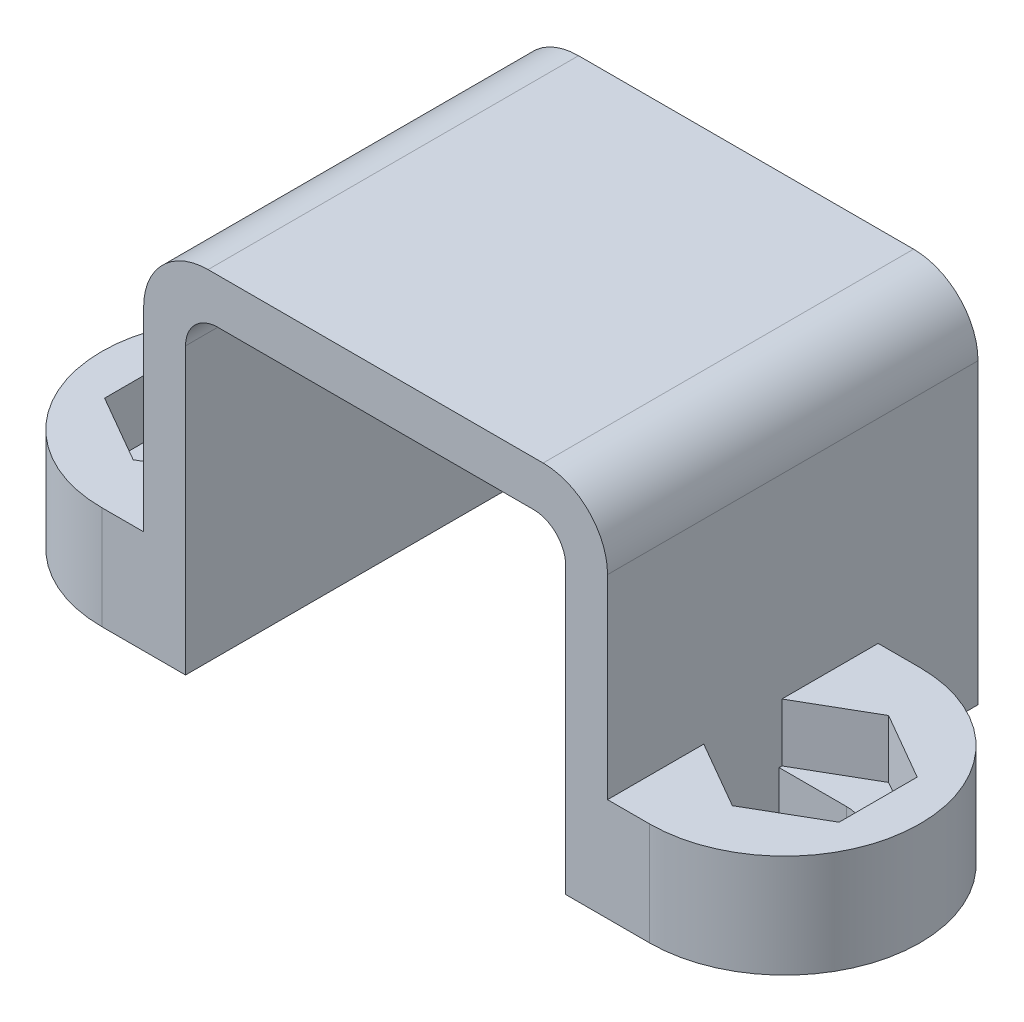
SolidWorks part; units mm, degrees
material "ABS PC"
ref_plane "前视基准面" through (0, 0, 0) normal (0, 0, 1) x (1, 0, 0)
ref_plane "上视基准面" through (0, 0, 0) normal (0, 1, 0) x (1, 0, 0)
ref_plane "右视基准面" through (0, 0, 0) normal (1, 0, 0) x (0, 0, -1)
sketch "草图1" plane through (0, 0, 0) normal (0, 0, 1) x (1, 0, 0)
  line L1 (14.4, 3.2) -> (14.4, 11.25)
  line L2 (14.4, 11.25) -> (0, 11.25)
  line L3 (0, 11.25) -> (0, 3.2)
  line L4 (1.3, 0) -> (1.3, 9.85)
  line L5 (1.3, 9.85) -> (13.1, 9.85)
  line L6 (13.1, 9.85) -> (13.1, 0)
  line L7 (0, 0) -> (1.3, 0)
  line L8 (19.9, 0) -> (19.9, 3.2)
  line L9 (19.9, 3.2) -> (14.4, 3.2)
  line L10 (0, 3.2) -> (-5.5, 3.2)
  line L11 (-5.5, 3.2) -> (-5.5, 0)
  line L12 (-5.5, 0) -> (0, 0)
  line L13 (14.4, 0) -> (19.9, 0)
  line L15 (13.1, 0) -> (14.4, 0)
  dimension "D1" = 14.4
  dimension "D2" = 9.85
  dimension "D3" = 11.25
  dimension "D4" = 11.8
  dimension "D5" = 11.25
  dimension "D6" = 3.2
  dimension "D7" = 3.2
  dimension "D8" = 5.5
  dimension "D9" = 5.5
extrude "凸台-拉伸1" add sketch "草图1" along normal blind 11.5
sketch "草图2" plane through (0, 3.2, 0) normal (0, 1, 0) x (1, 0, 0)
  line L3 (14.4, -11.5) -> (15.7, -11.5)
  line L5 (14.4, -11.5) -> (14.4, -3.1)
  line L6 (14.4, -11.5) -> (14.4, 0) construction
  line L7 (19.9, -11.5) -> (14.4, -11.5) construction
  line L9 (15.7, -3.1) -> (14.4, -3.1)
  arc A1 (15.7, -11.5) -> (15.7, -3.1) centre (15.7, -7.3) ccw
  line M8 (19.9, 0) -> (14.4, 0)
  line M9 (14.4, 0) -> (14.4, -11.5)
  line M10 (14.4, -11.5) -> (19.9, -11.5)
  line M11 (19.9, -11.5) -> (19.9, 0)
  dimension "D1" = 8.4
  dimension "D3" = 8.4
  dimension "D2" = 1.3
extrude "切除-拉伸1" cut sketch "草图2" against normal blind 11.5 contours A1 L9 M11 M8 M9 | A1 M10 M11
sketch "草图3" plane through (0, 3.2, 0) normal (0, 1, 0) x (1, 0, 0)
  line L0 (0, -11.5) -> (0, -3.1)
  line L1 (0, -11.5) -> (0, 0) construction
  line L2 (0, -11.5) -> (-5.5, -11.5) construction
  line L3 (0, -3.1) -> (-1.3, -3.1)
  line L5 (-1.3, -11.5) -> (0, -11.5)
  arc A0 (-1.3, -3.1) -> (-1.3, -11.5) centre (-1.3, -7.3) ccw
  line M5 (0, 0) -> (-5.5, 0)
  line M6 (-5.5, 0) -> (-5.5, -11.5)
  line M7 (-5.5, -11.5) -> (0, -11.5)
  line M8 (0, -11.5) -> (0, 0)
  dimension "D1" = 8.4
  dimension "D2" = 1.3
extrude "切除-拉伸2" cut sketch "草图3" against normal blind 11.5 contours A0 L3 M8 M5 M6 | A0 M6 M7
sketch "草图4" plane through (14.4, 0, 0) normal (1, 0, 0) x (0, 0, -1)
  line L1 (-3.1, 3.2) -> (-11.5, 3.2)
sketch "草图5" plane through (0, 3.2, 0) normal (0, 1, 0) x (1, 0, 0)
  line L1 (14.4, -3.1) -> (14.4, -11.5) construction
  line L2 (14.4, -3.1) -> (14.4, -7.3)
  line L4 (16.5, -6.175) -> (14.4, -6.175)
  line L5 (14.4, -6.175) -> (14.4, -8.425)
  line L6 (14.4, -8.425) -> (16.5, -8.425)
  line L7 (18.6, -6.0876) -> (16.5, -4.8751)
  line L8 (16.5, -4.8751) -> (14.4, -6.0876)
  line L9 (14.4, -6.0876) -> (14.4, -8.5124)
  line L10 (14.4, -8.5124) -> (16.5, -9.7249)
  line L11 (16.5, -9.7249) -> (18.6, -8.5124)
  line L12 (18.6, -8.5124) -> (18.6, -6.0876)
  arc A0 (16.5, -8.425) -> (16.5, -6.175) centre (16.5, -7.3) ccw
  circle A1 centre (16.5, -7.3) radius 2.1 construction
  dimension "D2" = 2.25
  dimension "D1" = 2.1
extrude "切除-拉伸3" cut sketch "草图5" against normal blind 1.8 contours L7 L8 L9 L10 L11 L12
sketch "草图7" plane through (0, 1.4, 0) normal (0, 1, 0) x (1, 0, 0)
  line L0 (14.4, -8.5124) -> (14.4, -6.0876)
  line L2 (16.5, -6.175) -> (14.4, -6.175)
  line L4 (14.4, -6.175) -> (14.4, -8.425)
  line L5 (16.5, -8.425) -> (14.4, -8.425)
  line L7 (16.5, -6.175) -> (14.4, -6.175)
  line L8 (16.5, -8.425) -> (14.4, -8.425)
  arc A0 (16.5, -8.425) -> (16.5, -6.175) centre (16.5, -7.3) ccw
  dimension "D2" = 2.25
sketch "草图8" plane through (0, 3.2, 0) normal (0, 1, 0) x (1, 0, 0)
  line L0 (0, -3.1) -> (0, -11.5)
  line L1 (0, -7.3) -> (-2.1, -7.3)
  line L2 (-4.2, -6.0876) -> (-4.2, -8.5124)
  line L4 (0, -6.0876) -> (-2.1, -4.8751)
  line L5 (-2.1, -4.8751) -> (-4.2, -6.0876)
  line L6 (-4.2, -6.0876) -> (-4.2, -8.5124)
  line L7 (-4.2, -8.5124) -> (-2.1, -9.7249)
  line L8 (-2.1, -9.7249) -> (0, -8.5124)
  line L9 (0, -8.5124) -> (0, -6.0876) [skipped]
  line L10 (-2.1, -9.7249) -> (0, -8.5124)
  line L11 (0, -6.0876) -> (-2.1, -4.8751)
  line L12 (-4.2, -6.0876) -> (-4.2, -8.5124)
  line L13 (0, -6.0876) -> (0, -8.5124)
  circle A0 centre (-2.1, -7.3) radius 2.1 construction
  dimension "D1" = 2.1
extrude "切除-拉伸4" cut sketch "草图8" against normal blind 1.8
sketch "草图10" plane through (0, 1.4, 0) normal (0, 1, 0) x (1, 0, 0)
  line L0 (0, -6.0876) -> (0, -8.5124)
  line L1 (0, -8.5124) -> (0, -6.0876) construction
  line L2 (0, -6.175) -> (0, -8.425)
  line L4 (-2.1, -8.425) -> (0, -8.425)
  line L5 (-2.1, -8.425) -> (0, -8.425)
  line L6 (-2.1, -6.175) -> (0, -6.175)
  line L8 (-2.1, -6.175) -> (0, -6.175)
  arc A0 (-2.1, -6.175) -> (-2.1, -8.425) centre (-2.1, -7.3) ccw
  dimension "D2" = 2.25
extrude "切除-拉伸5" cut sketch "草图10" against normal blind 1.8 contours L6 A0 L4 L0
extrude "切除-拉伸6" cut sketch "草图7" against normal blind 1.8 contours L5 A0 L2 L0
fillet "圆角1" radius 2 1 edges at (0, 11.25, 5.75)
fillet "圆角2" radius 2 1 edges at (14.4, 11.25, 5.75)
fillet "圆角3" radius 1 1 edges at (1.3, 9.85, 5.75)
fillet "圆角4" radius 1 1 edges at (13.1, 9.85, 5.75)
